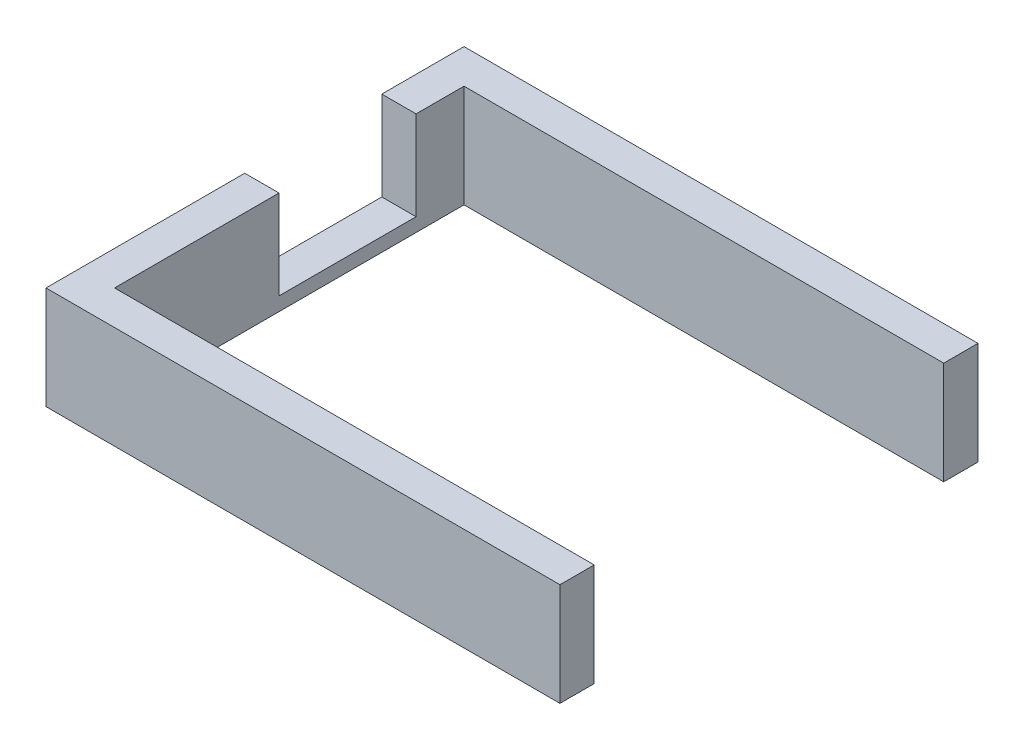
SolidWorks part; units mm, degrees
ref_plane "Front Plane" through (0, 0, 0) normal (0, 0, 1) x (1, 0, 0)
ref_plane "Top Plane" through (0, 0, 0) normal (0, 1, 0) x (1, 0, 0)
ref_plane "Right Plane" through (0, 0, 0) normal (1, 0, 0) x (0, 0, -1)
sketch "Sketch1" plane through (0, 0, 0) normal (0, 1, 0) x (1, 0, 0)
  line L0 (35, -25.5) -> (35, -30.5)
  line L1 (-35, 25.5) -> (35, 25.5)
  line L2 (-35, 25.5) -> (-35, -25.5)
  line L3 (-35, -25.5) -> (35, -25.5)
  line L4 (35, 25.5) -> (35, 30.5)
  line L5 (-35, 25.5) -> (35, -25.5) construction
  line L6 (-35, -25.5) -> (35, 25.5) construction
  line L7 (-40, 30.5) -> (35, 30.5)
  line L8 (-40, 30.5) -> (-40, -30.5)
  line L9 (-40, -30.5) -> (35, -30.5)
  point P0 (0, 0)
  point P6 (0, 0)
  dimension "D1" = 51
  dimension "D2" = 70
  dimension "D3" = 5
  dimension "D4" = 75
  dimension "D5" = 5
  dimension "D6" = 5
  dimension "D7" = 75
extrude "Boss-Extrude1" add sketch "Sketch1" along normal blind 15
sketch "Sketch2" plane through (0, 15, 0) normal (0, 1, 0) x (1, 0, 0)
  line L0 (-35, -25.5) -> (-35, 25.5) construction
  line L1 (-40, 18.5) -> (-35, 18.5)
  line L2 (-40, 18.5) -> (-40, -1.5)
  line L3 (-40, -1.5) -> (-35, -1.5)
  line L4 (-35, 18.5) -> (-35, -1.5)
  line L5 (-40, 18.5) -> (-35, -1.5) construction
  line L6 (-40, -1.5) -> (-35, 18.5) construction
  line L7 (-35, 25.5) -> (35, 25.5) construction
  line L8 (-40, 30.5) -> (-40, -30.5) construction
  point P0 (-37.5, 8.5)
  dimension "D1" = 7
  dimension "D2" = 0
  dimension "D3" = 20
extrude "Cut-Extrude1" cut sketch "Sketch2" against normal blind 13
